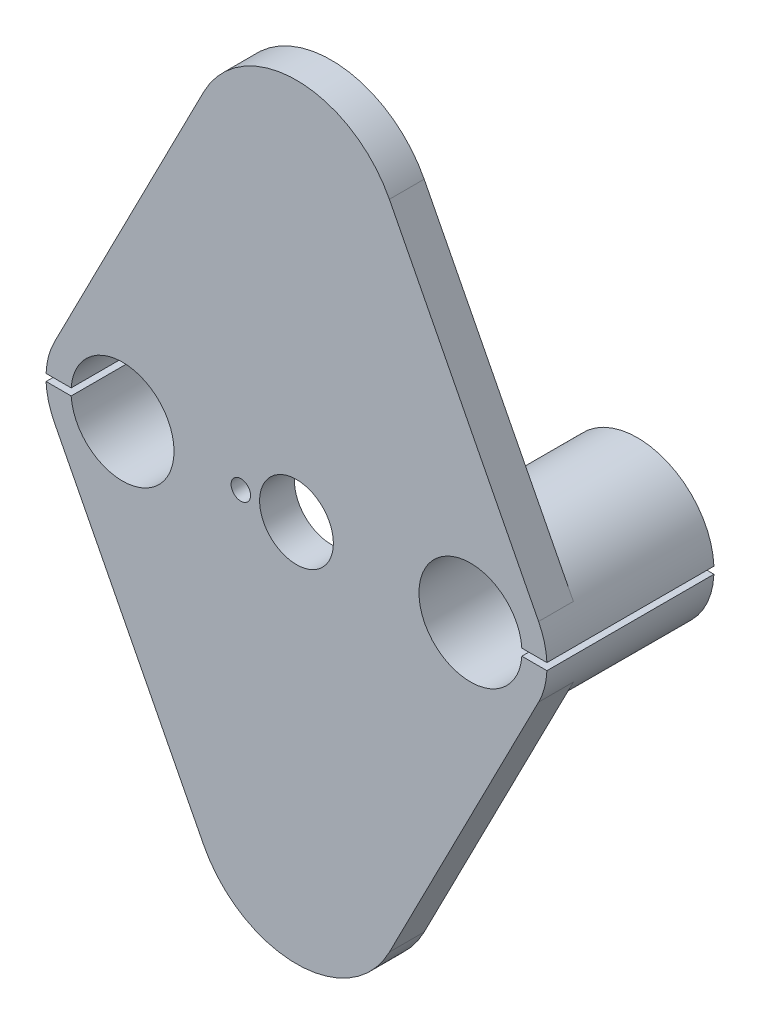
SolidWorks part; units mm, degrees
ref_plane "Płaszczyzna przednia" through (0, 0, 0) normal (0, 0, 1) x (1, 0, 0)
ref_plane "Płaszczyzna górna" through (0, 0, 0) normal (0, 1, 0) x (1, 0, 0)
ref_plane "Płaszczyzna prawa" through (0, 0, 0) normal (1, 0, 0) x (0, 0, -1)
sketch "Sketch1" plane through (0, 0, 0) normal (0, 0, 1) x (1, 0, 0)
  line L0 (0, 110) -> (0, 0) construction
  line L1 (-36, 55) -> (36, 55) construction
  line L2 (-34.7888, 60.018) -> (-13.3483, 101.8427)
  line L3 (-34.7888, 49.982) -> (-13.3483, 8.1573)
  line L4 (34.7888, 49.982) -> (13.3483, 8.1573)
  line L5 (34.7888, 60.018) -> (13.3483, 101.8427)
  arc A0 (13.3483, 101.8427) -> (-13.3483, 101.8427) centre (0, 95) ccw
  arc A1 (13.3483, 8.1573) -> (-13.3483, 8.1573) centre (0, 15) cw
  arc A2 (-34.7888, 60.018) -> (-34.7888, 49.982) centre (-25, 55) ccw
  arc A3 (34.7888, 60.018) -> (34.7888, 49.982) centre (25, 55) cw
  circle A4 centre (0, 55) radius 5.3
  point P3 (0, 55)
  dimension "D4" = 30
  dimension "D5" = 22
  dimension "D6" = 10.6
  dimension "D1" = 110
  dimension "D2" = 72
  dimension "D3" = 72
extrude "Boss-Extrude1" add sketch "Sketch1" along normal blind 5
sketch "Sketch2" plane through (0, 0, 0) normal (0, 0, -1) x (-1, 0, 0)
  circle A0 centre (-25, 55) radius 11
  circle A1 centre (25, 55) radius 11
  arc A4 (-34.7888, 60.018) -> (-34.7888, 49.982) centre (-25, 55) ccw construction
  arc A5 (34.7888, 49.982) -> (34.7888, 60.018) centre (25, 55) ccw construction
  dimension "D1" = 22
  dimension "D2" = 22
extrude "Boss-Extrude2" add sketch "Sketch2" along normal blind 19
sketch "Sketch3" plane through (0, 0, -19) normal (0, 0, -1) x (-1, 0, 0)
  circle A0 centre (-25, 55) radius 7.4
  circle A1 centre (25, 55) radius 7.4
  arc A2 (-34.7888, 49.982) -> (-34.7888, 60.018) centre (-25, 55) ccw construction
  point P5 (-24.4405, 51.7357)
  dimension "D1" = 14.8
extrude "Cut-Extrude1" cut sketch "Sketch3" against normal up to next
sketch "Sketch4" plane through (0, 0, 5) normal (0, 0, 1) x (1, 0, 0)
  line L0 (-25, 55) -> (25, 55) construction
  circle A0 centre (-8, 55) radius 1.4
  circle A3 centre (0, 55) radius 5.3 construction
  point P5 (0, 55)
  point P6 (-0.6203, 55)
  point P7 (0, 0)
  dimension "3,5" = 2.8
  dimension "D1" = 8
ref_plane "Plane1" through (36, 0, 0) normal (1, 0, 0) x (0, 0, -1)
sketch "Sketch6" plane through (36, 0, 0) normal (1, 0, 0) x (0, 0, -1)
  line L0 (-5, 60.018) -> (-5, 49.982) construction
  line L1 (-5, 55.5) -> (19, 55.5)
  line L2 (-5, 55.5) -> (-5, 54.5)
  line L3 (-5, 54.5) -> (19, 54.5)
  line L4 (19, 55.5) -> (19, 54.5)
  line L5 (7, 54.5) -> (7, 55.5) construction
  line L6 (-5, 55) -> (19, 55) construction
  line L7 (19, 44) -> (19, 66) construction
  point P8 (19, 66)
  point P9 (19, 44)
  point P236 (7, 55)
  dimension "D1" = 22
  dimension "D2" = 1
extrude "Cut-Extrude2" cut sketch "Sketch6" against normal up to next
mirror "Mirror1" about plane through (0, 0, 0) normal (1, 0, 0) of "Cut-Extrude2"
extrude "Cut-Extrude3" cut sketch "Sketch4" against normal up to next
